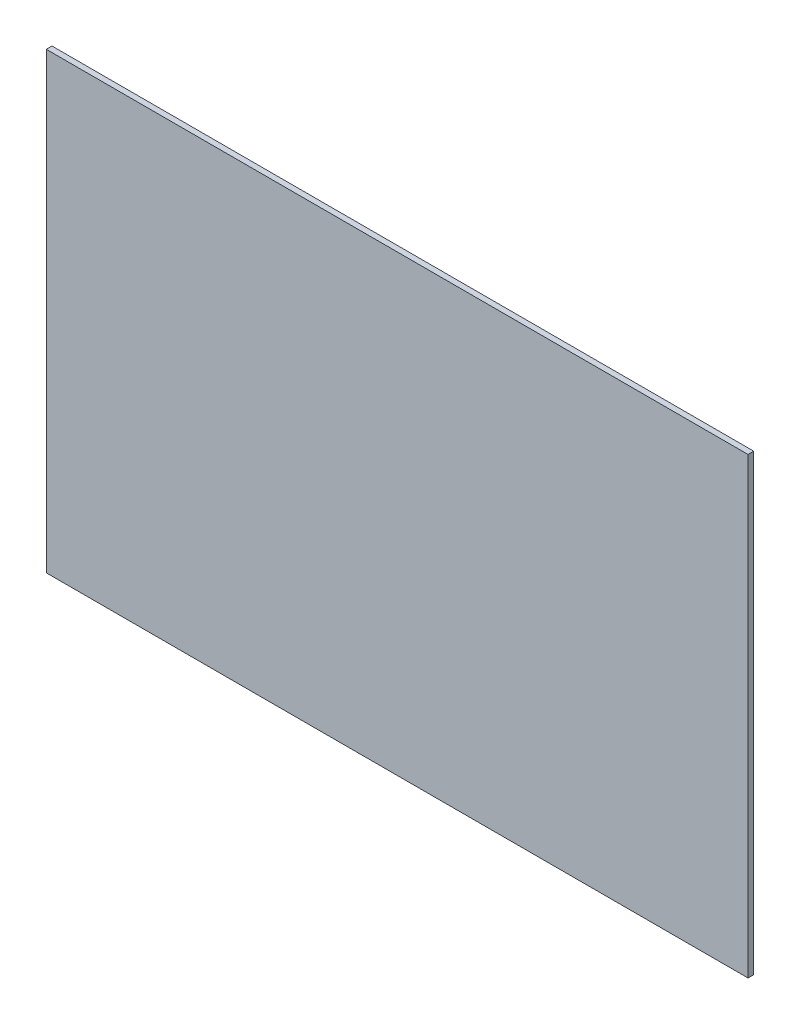
SolidWorks part; units mm, degrees
ref_plane "Plan de face" through (0, 0, 0) normal (0, 0, 1) x (1, 0, 0)
ref_plane "Plan de dessus" through (0, 0, 0) normal (0, 1, 0) x (1, 0, 0)
ref_plane "Plan de droite" through (0, 0, 0) normal (1, 0, 0) x (0, 0, -1)
sketch "Esquisse1" plane through (0, 0, 0) normal (0, 0, 1) x (1, 0, 0)
  line L1 (-399.85, -258.35) -> (399.85, -258.35)
  line L2 (-399.85, -258.35) -> (-399.85, 258.35)
  line L3 (-399.85, 258.35) -> (399.85, 258.35)
  line L4 (399.85, -258.35) -> (399.85, 258.35)
  line L5 (-399.85, -258.35) -> (399.85, 258.35) construction
  line L6 (-399.85, 258.35) -> (399.85, -258.35) construction
  point P0 (0, 0)
  dimension "D1" = 516.7
  dimension "D2" = 799.7
extrude "Boss.-Extru.1" add sketch "Esquisse1" along normal blind 6.5
